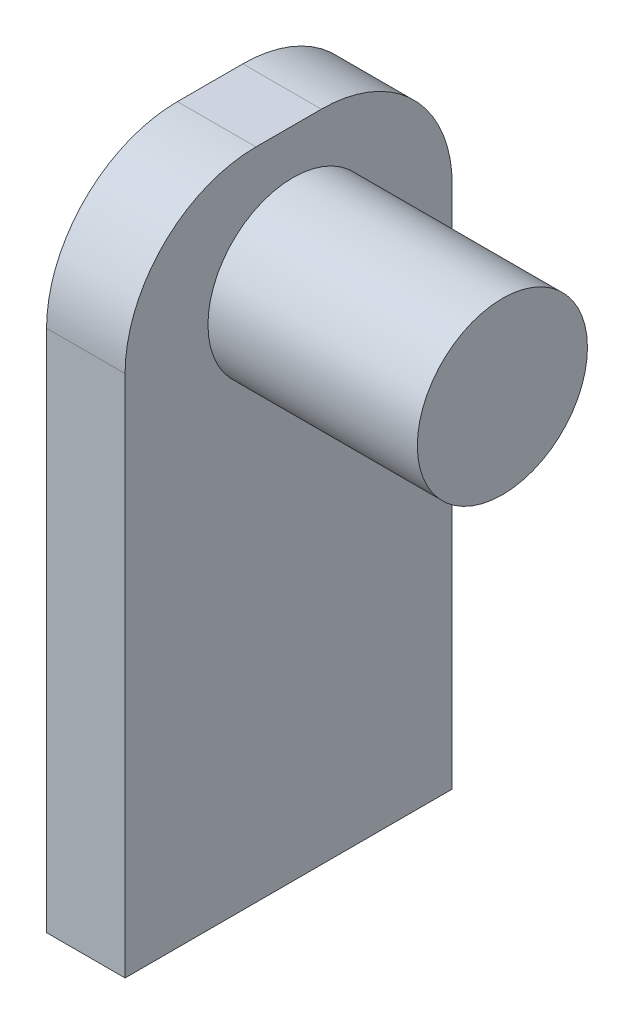
SolidWorks part; units mm, degrees
ref_plane "Front Plane" through (0, 0, 0) normal (0, 0, 1) x (1, 0, 0)
ref_plane "Top Plane" through (0, 0, 0) normal (0, 1, 0) x (1, 0, 0)
ref_plane "Right Plane" through (0, 0, 0) normal (1, 0, 0) x (0, 0, -1)
sketch "Sketch1" plane through (0, 0, 0) normal (1, 0, 0) x (0, 0, -1)
  line L1 (-10, 0) -> (-15, 0)
  line L2 (0, -10) -> (0, -50)
  line L3 (0, -50) -> (-25, -50)
  line L4 (-25, -10) -> (-25, -50)
  arc A0 (-10, 0) -> (0, -10) centre (-10, -10) cw
  arc A1 (-15, 0) -> (-25, -10) centre (-15, -10) ccw
  point P7 (0, 0)
  point P10 (-25, 0)
  dimension "D3" = 10
  dimension "D1" = 25
  dimension "D2" = 50
extrude "Boss-Extrude1" add sketch "Sketch1" along normal blind 6
sketch "Sketch2" plane through (6, 0, 0) normal (1, 0, 0) x (0, 0, -1)
  circle A0 centre (-12.1654, -9.9414) radius 6.5
  dimension "D1" = 13
extrude "Boss-Extrude2" add sketch "Sketch2" along normal blind 16
sketch "Sketch3" plane through (0, 0, 0) normal (-1, 0, 0) x (0, 0, 1)
  circle A0 centre (12.9016, -42.8026) radius 2.4094
extrude "Cut-Extrude1" cut sketch "Sketch3" against normal blind 2.5
